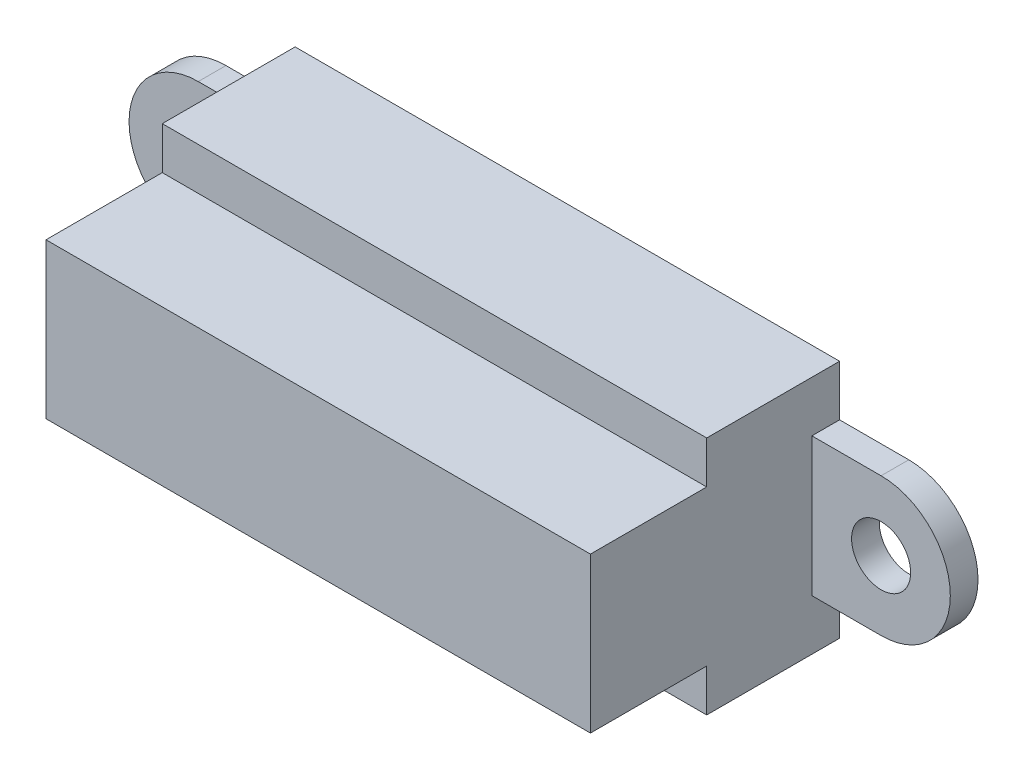
SolidWorks part; units mm, degrees
ref_plane "正面" through (0, 0, 0) normal (0, 0, 1) x (1, 0, 0)
ref_plane "平面" through (0, 0, 0) normal (0, 1, 0) x (1, 0, 0)
ref_plane "右側面" through (0, 0, 0) normal (1, 0, 0) x (0, 0, -1)
sketch "ｽｹｯﾁ1" plane through (0, 0, 0) normal (0, 0, 1) x (1, 0, 0)
  line L0 (0, 0) -> (37, 0) construction
  line L1 (0, 3.75) -> (37, 3.75)
  line L2 (0, -3.75) -> (37, -3.75)
  arc A0 (0, 3.75) -> (0, -3.75) centre (0, 0) ccw
  arc A1 (37, -3.75) -> (37, 3.75) centre (37, 0) ccw
  circle A2 centre (0, 0) radius 1.6
  circle A3 centre (37, 0) radius 1.6
  point P3 (18.5, 0)
  dimension "D1" = 37
  dimension "D2" = 3.75
  dimension "D3" = 3.2
  dimension "D4" = 3.2
extrude "ﾎﾞｽ - 押し出し1" add sketch "ｽｹｯﾁ1" along normal blind 1.5
sketch "ｽｹｯﾁ2" plane through (0, 0, 0) normal (0, 0, -1) x (-1, 0, 0)
  line L0 (-37, 0) -> (0, 0)
  line L2 (-33.25, -6.5) -> (-3.75, -6.5)
  line L3 (-33.25, -6.5) -> (-33.25, 6.5)
  line L4 (-33.25, 6.5) -> (-3.75, 6.5)
  line L5 (-3.75, -6.5) -> (-3.75, 6.5)
  line L6 (-33.25, -6.5) -> (-3.75, 6.5) construction
  line L7 (-33.25, 6.5) -> (-3.75, -6.5) construction
  point P4 (-18.5, 0)
  line M4 (0, 3.75) -> (-37, 3.75)
  line M6 (-37, -3.75) -> (0, -3.75)
  dimension "D1" = 13
  dimension "D2" = 29.5
extrude "ﾎﾞｽ - 押し出し2" add sketch "ｽｹｯﾁ2" against normal blind 7.2 contours L5 L0 L3 M6 | L0 L5 L3 M4 | L5 L4 L3 M4 | L2 L5 L3 M6
sketch "ｽｹｯﾁ3" plane through (0, 0, 7.2) normal (0, 0, 1) x (1, 0, 0)
  line L0 (3.75, -6.5) -> (3.75, 6.5) construction
  line L1 (33.25, -4.2) -> (3.75, -4.2)
  line L2 (33.25, -4.2) -> (33.25, 4.2)
  line L3 (33.25, 4.2) -> (3.75, 4.2)
  line L4 (3.75, -4.2) -> (3.75, 4.2)
  line L5 (33.25, -4.2) -> (3.75, 4.2) construction
  line L6 (33.25, 4.2) -> (3.75, -4.2) construction
  line L7 (0, 0) -> (37, 0) construction
  line L8 (33.25, -6.5) -> (33.25, 6.5) construction
  point P0 (18.5, 0)
  point P11 (0, 0)
  point P12 (33.25, 4.2)
  dimension "D1" = 8.4
extrude "ﾎﾞｽ - 押し出し3" add sketch "ｽｹｯﾁ3" along normal blind 6.3
